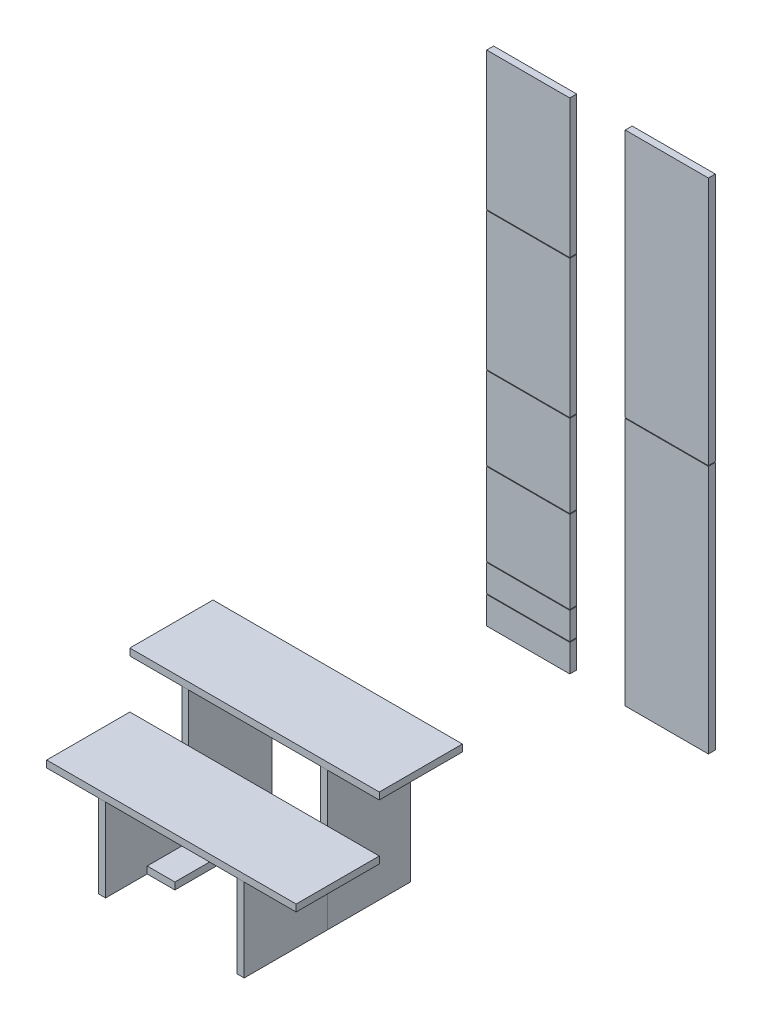
SolidWorks part; units mm, degrees
other "DetailItem1"
ref_plane "Front Plane" through (0, 0, 0) normal (0, 0, 1) x (1, 0, 0)
ref_plane "Top Plane" through (0, 0, 0) normal (0, 1, 0) x (1, 0, 0)
ref_plane "Right Plane" through (0, 0, 0) normal (1, 0, 0) x (0, 0, -1)
sketch "Sketch1" plane through (0, 0, 0) normal (0, 1, 0) x (1, 0, 0)
  line L0 (-254, 0) -> (254, 0) construction
  line L2 (-266.7, 152.4) -> (-241.3, 152.4)
  line L3 (-266.7, 152.4) -> (-266.7, -152.4)
  line L4 (-266.7, -152.4) -> (-241.3, -152.4)
  line L5 (-241.3, 152.4) -> (-241.3, -152.4)
  line L6 (-266.7, 152.4) -> (-241.3, -152.4) construction
  line L7 (-266.7, -152.4) -> (-241.3, 152.4) construction
  line L8 (241.3, 152.4) -> (266.7, 152.4)
  line L9 (241.3, 152.4) -> (241.3, -152.4)
  line L10 (241.3, -152.4) -> (266.7, -152.4)
  line L11 (266.7, 152.4) -> (266.7, -152.4)
  line L12 (241.3, 152.4) -> (266.7, -152.4) construction
  line L13 (241.3, -152.4) -> (266.7, 152.4) construction
  dimension "D1" = 25.4
  dimension "D2" = 304.8
  dimension "D3" = 508
extrude "Boss-Extrude1" add sketch "Sketch1" along normal blind 508
sketch "Sketch2" plane through (0, 508, 0) normal (0, 1, 0) x (1, 0, 0)
  line L0 (-241.3, 152.4) -> (-266.7, 152.4) construction
  line L1 (-457.2, -152.4) -> (457.2, -152.4)
  line L2 (-457.2, -152.4) -> (-457.2, 152.4)
  line L3 (-457.2, 152.4) -> (457.2, 152.4)
  line L4 (457.2, -152.4) -> (457.2, 152.4)
  line L5 (-457.2, -152.4) -> (457.2, 152.4) construction
  line L6 (-457.2, 152.4) -> (457.2, -152.4) construction
  point P0 (0, 0)
  dimension "D1" = 914.4
extrude "Boss-Extrude2" add sketch "Sketch2" along normal blind 25.4 separate body
sketch "Sketch3" plane through (0, 0, 0) normal (0, 1, 0) x (1, 0, 0)
  line L0 (-254, -304.8) -> (254, -304.8) construction
  line L1 (-457.2, -152.4) -> (457.2, -152.4) construction
  line L2 (-266.7, -152.4) -> (-241.3, -152.4)
  line L3 (-266.7, -152.4) -> (-266.7, -457.2)
  line L4 (-266.7, -457.2) -> (-241.3, -457.2)
  line L5 (-241.3, -152.4) -> (-241.3, -457.2)
  line L6 (-266.7, -152.4) -> (-241.3, -457.2) construction
  line L7 (-266.7, -457.2) -> (-241.3, -152.4) construction
  line L8 (241.3, -152.4) -> (266.7, -152.4)
  line L9 (241.3, -152.4) -> (241.3, -457.2)
  line L10 (241.3, -457.2) -> (266.7, -457.2)
  line L11 (266.7, -152.4) -> (266.7, -457.2)
  line L12 (241.3, -152.4) -> (266.7, -457.2) construction
  line L13 (241.3, -457.2) -> (266.7, -152.4) construction
  point P2 (0, -304.8)
  dimension "D1" = 25.4
  dimension "D2" = 304.8
  dimension "D3" = 508
extrude "Boss-Extrude3" add sketch "Sketch3" along normal blind 304.8 separate body
sketch "Sketch4" plane through (0, 304.8, 0) normal (0, 1, 0) x (1, 0, 0)
  line L0 (-457.2, -152.4) -> (457.2, -152.4) construction
  line L1 (-457.2, -457.2) -> (457.2, -457.2)
  line L2 (-457.2, -457.2) -> (-457.2, -152.4)
  line L3 (-457.2, -152.4) -> (457.2, -152.4)
  line L4 (457.2, -457.2) -> (457.2, -152.4)
  line L5 (-457.2, -457.2) -> (457.2, -152.4) construction
  line L6 (-457.2, -152.4) -> (457.2, -457.2) construction
  line L7 (-266.7, -457.2) -> (-241.3, -457.2) construction
  point P0 (0, -304.8)
  dimension "D1" = 914.4
extrude "Boss-Extrude4" add sketch "Sketch4" along normal blind 25.4 separate body
sketch "Sketch5" plane through (0, 0, 0) normal (0, 1, 0) x (1, 0, 0)
  line L0 (0, 0) -> (0, 1117.6) construction
  line L1 (-254, 1117.6) -> (254, 1117.6) construction
  line L3 (-406.4, 1130.3) -> (-101.6, 1130.3)
  line L4 (-406.4, 1130.3) -> (-406.4, 1104.9)
  line L5 (-406.4, 1104.9) -> (-101.6, 1104.9)
  line L6 (-101.6, 1130.3) -> (-101.6, 1104.9)
  line L7 (-406.4, 1130.3) -> (-101.6, 1104.9) construction
  line L8 (-406.4, 1104.9) -> (-101.6, 1130.3) construction
  line L9 (101.6, 1130.3) -> (406.4, 1130.3)
  line L10 (101.6, 1130.3) -> (101.6, 1104.9)
  line L11 (101.6, 1104.9) -> (406.4, 1104.9)
  line L12 (406.4, 1130.3) -> (406.4, 1104.9)
  line L13 (101.6, 1130.3) -> (406.4, 1104.9) construction
  line L14 (101.6, 1104.9) -> (406.4, 1130.3) construction
  point P5 (0, 1117.6)
  dimension "D1" = 25.4
  dimension "D2" = 304.8
  dimension "D3" = 25.4
  dimension "D4" = 304.8
  dimension "D5" = 1117.6
  dimension "D6" = 508
extrude "Boss-Extrude5" add sketch "Sketch5" along normal blind 1828.8 separate body
sketch "Sketch6" plane through (0, 0, -1130.3) normal (0, 0, -1) x (-1, 0, 0)
  line L0 (-406.4, 914.4) -> (-101.6, 914.4)
  line L1 (-406.4, 1828.8) -> (-406.4, 0) construction
  line L2 (-101.6, 1828.8) -> (-101.6, 0) construction
  line L3 (101.6, 1320.8) -> (406.4, 1320.8)
  line L4 (101.6, 1828.8) -> (101.6, 0) construction
  line L5 (406.4, 1828.8) -> (406.4, 0) construction
  line L6 (101.6, 812.8) -> (406.4, 812.8)
  line L7 (101.6, 508) -> (406.4, 508)
  line L8 (101.6, 203.2) -> (406.4, 203.2)
  line L9 (101.6, 101.6) -> (406.4, 101.6)
  line L10 (101.6, 1828.8) -> (406.4, 1828.8) construction
  line L11 (101.6, 0) -> (406.4, 0) construction
  dimension "D1" = 508
  dimension "D2" = 508
  dimension "D3" = 304.8
  dimension "D4" = 304.8
  dimension "D5" = 101.6
sketch "Sketch7" plane through (0, 0, 0) normal (0, -1, 0) x (1, 0, 0)
  line L0 (-241.3, 152.4) -> (241.3, 152.4) construction
  line L1 (241.3, -152.4) -> (241.3, 152.4) construction
  line L2 (-241.3, 304.8) -> (241.3, 304.8)
  line L3 (-241.3, 304.8) -> (-241.3, 0)
  line L4 (-241.3, 0) -> (241.3, 0)
  line L5 (241.3, 304.8) -> (241.3, 0)
  line L6 (-241.3, 304.8) -> (241.3, 0) construction
  line L7 (-241.3, 0) -> (241.3, 304.8) construction
  line L8 (-139.7, 304.8) -> (-139.7, 0)
  line L9 (139.7, 304.8) -> (139.7, 0)
  point P4 (0, 152.4)
  line M7 (-241.3, 152.4) -> (-241.3, 457.2)
  dimension "D1" = 304.8
  dimension "D2" = 101.6
  dimension "D3" = 101.6
extrude "Boss-Extrude6" add sketch "Sketch7" against normal blind 25.4 separate body contours L8 L2 L3 L4 M7 | L2 L9 L4 L5
extrude "Cut-Extrude-Thin1" cut sketch "Sketch6" against normal blind 25.4 thin thin type mid plane wall 2.54
equation "\"D3@Sketch1\"=36-16"
equation "\"D3@Sketch3\"=36-16"
